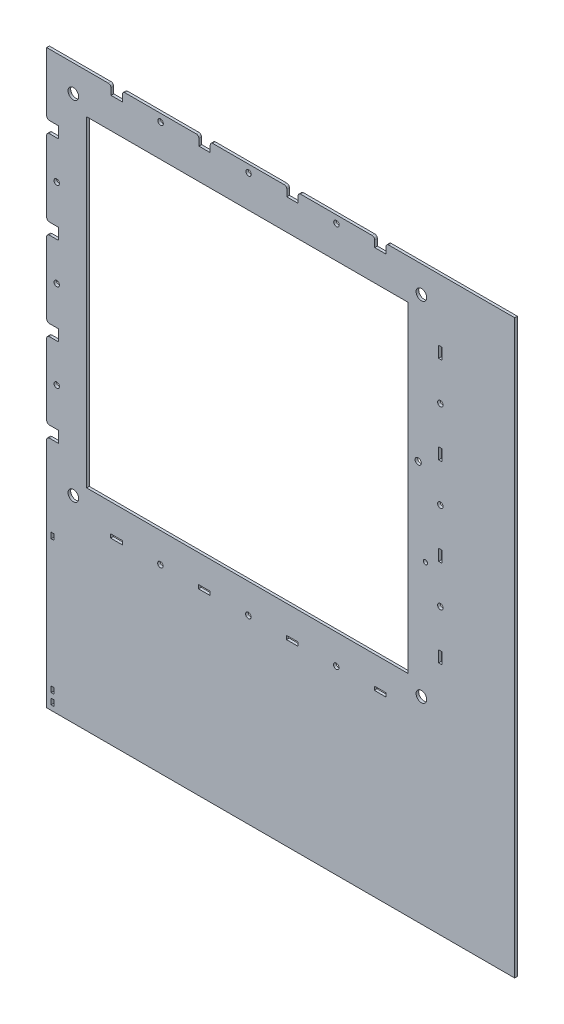
SolidWorks part; units mm, degrees
ref_plane "前视基准面" through (0, 0, 0) normal (0, 0, 1) x (1, 0, 0)
ref_plane "上视基准面" through (0, 0, 0) normal (0, 1, 0) x (1, 0, 0)
ref_plane "右视基准面" through (0, 0, 0) normal (1, 0, 0) x (0, 0, -1)
sketch "草图1" plane through (0, 0, 0) normal (0, 0, 1) x (1, 0, 0)
  line L0 (95.3243, -141.495) -> (104.1243, -141.495)
  line L1 (0.7243, -148.895) -> (0.7243, -142.895) construction
  line L2 (0.7243, -142.895) -> (33.7243, -142.895) construction
  line L3 (33.7243, -142.895) -> (66.7243, -142.895) construction
  line L4 (29.3243, -141.495) -> (38.1243, -141.495)
  line L5 (29.3243, -141.495) -> (29.3243, -144.295)
  line L6 (29.3243, -144.295) -> (38.1243, -144.295)
  line L7 (38.1243, -141.495) -> (38.1243, -144.295)
  line L8 (29.3243, -141.495) -> (38.1243, -144.295) construction
  line L9 (29.3243, -144.295) -> (38.1243, -141.495) construction
  line L10 (66.7243, -142.895) -> (99.7243, -142.895) construction
  line L11 (95.3243, -141.495) -> (95.3243, -144.295)
  line L12 (95.3243, -144.295) -> (104.1243, -144.295)
  line L13 (95.3243, -144.295) -> (104.1243, -141.495) construction
  line L14 (104.1243, -144.295) -> (104.1243, -141.495)
  line L15 (-36.6757, -141.495) -> (-36.6757, -144.295)
  line L16 (-27.8757, -141.495) -> (-36.6757, -141.495)
  line L17 (-27.8757, -141.495) -> (-27.8757, -144.295)
  line L18 (-27.8757, -144.295) -> (-36.6757, -144.295)
  line L19 (-93.8757, -141.495) -> (-93.8757, -144.295)
  line L20 (-102.6757, -144.295) -> (-102.6757, -141.495)
  line L21 (-93.8757, -141.495) -> (-102.6757, -141.495)
  line L22 (-93.8757, -144.295) -> (-102.6757, -144.295)
  line L23 (-141.8757, 95.705) -> (-141.8757, 104.205)
  line L24 (-144.3757, 95.705) -> (-144.3757, 104.205)
  line L25 (-144.3757, 104.205) -> (-141.8757, 104.205)
  line L26 (-141.8757, 95.705) -> (-144.3757, 95.705)
  line L27 (-141.8757, 29.705) -> (-141.8757, 38.205)
  line L28 (-141.8757, 38.205) -> (-144.3757, 38.205)
  line L29 (-144.3757, 29.705) -> (-144.3757, 38.205)
  line L30 (-141.8757, 29.705) -> (-144.3757, 29.705)
  line L31 (-141.8757, -27.795) -> (-144.3757, -27.795)
  line L32 (-141.8757, -27.795) -> (-141.8757, -36.295)
  line L33 (-144.3757, -27.795) -> (-144.3757, -36.295)
  line L34 (-141.8757, -36.295) -> (-144.3757, -36.295)
  line L35 (-141.8757, -93.795) -> (-141.8757, -102.295)
  line L36 (-144.3757, -93.795) -> (-144.3757, -102.295)
  line L37 (-141.8757, -93.795) -> (-144.3757, -93.795)
  line L38 (-144.3757, -102.295) -> (-141.8757, -102.295)
  line L39 (95.6243, 143.705) -> (104.1243, 143.705)
  line L40 (95.6243, 146.205) -> (104.1243, 146.205)
  line L41 (104.1243, 146.205) -> (104.1243, 143.705)
  line L42 (95.6243, 143.705) -> (95.6243, 146.205)
  line L43 (29.6243, 143.705) -> (38.1243, 143.705)
  line L44 (38.1243, 143.705) -> (38.1243, 146.205)
  line L45 (29.6243, 146.205) -> (38.1243, 146.205)
  line L46 (29.6243, 143.705) -> (29.6243, 146.205)
  line L47 (-27.8757, 143.705) -> (-27.8757, 146.205)
  line L48 (-27.8757, 143.705) -> (-36.3757, 143.705)
  line L49 (-27.8757, 146.205) -> (-36.3757, 146.205)
  line L50 (-36.3757, 143.705) -> (-36.3757, 146.205)
  line L51 (-93.8757, 143.705) -> (-102.3757, 143.705)
  line L52 (-93.8757, 146.205) -> (-102.3757, 146.205)
  line L53 (-93.8757, 143.705) -> (-93.8757, 146.205)
  line L54 (-102.3757, 146.205) -> (-102.3757, 143.705)
  line L55 (143.6243, -93.795) -> (143.6243, -102.295)
  line L56 (146.1243, -93.795) -> (146.1243, -102.295)
  line L57 (146.1243, -102.295) -> (143.6243, -102.295)
  line L58 (143.6243, -93.795) -> (146.1243, -93.795)
  line L59 (143.6243, -27.795) -> (143.6243, -36.295)
  line L60 (143.6243, -36.295) -> (146.1243, -36.295)
  line L61 (146.1243, -27.795) -> (146.1243, -36.295)
  line L62 (143.6243, -27.795) -> (146.1243, -27.795)
  line L63 (143.6243, 29.705) -> (146.1243, 29.705)
  line L64 (143.6243, 29.705) -> (143.6243, 38.205)
  line L65 (146.1243, 29.705) -> (146.1243, 38.205)
  line L66 (143.6243, 38.205) -> (146.1243, 38.205)
  line L67 (143.6243, 95.705) -> (143.6243, 104.205)
  line L68 (146.1243, 95.705) -> (146.1243, 104.205)
  line L69 (143.6243, 95.705) -> (146.1243, 95.705)
  line L70 (146.1243, 104.205) -> (143.6243, 104.205)
  line L71 (50.2243, -142.895) -> (50.2243, -127.895) construction
  line L72 (17.2243, -142.895) -> (17.2243, -127.895) construction
  line L73 (120.6507, 120.6507) -> (-120.6507, 120.6507)
  line L75 (99.7243, -142.895) -> (104.1243, -144.295) construction
  line L76 (150.6507, -150.6507) -> (150.6507, 150.6507) construction
  line L78 (-150.6507, -150.6507) -> (-150.6507, 150.6507)
  line L79 (150.6507, -150.6507) -> (-150.6507, 150.6507) construction
  line L80 (150.6507, 150.6507) -> (-150.6507, -150.6507) construction
  line L81 (-120.6507, -120.6507) -> (-120.6507, 120.6507)
  line L82 (120.6507, -120.6507) -> (-120.6507, -120.6507)
  line L83 (120.6507, -120.6507) -> (120.6507, 120.6507)
  line L84 (-150.6507, 150.6507) -> (-150.6507, 277.9507) construction
  line L85 (-150.6507, 277.9507) -> (150.6507, 277.9507) construction
  line L86 (150.6507, 277.9507) -> (150.6507, 150.6507) construction
  line L87 (150.6507, 150.6507) -> (-150.6507, 150.6507)
  line L88 (150.6507, 150.6507) -> (-150.6507, 150.6507) construction
  line L89 (-120.6507, 180.6507) -> (-120.6507, 247.9507) construction
  line L90 (-120.6507, 247.9507) -> (120.6507, 247.9507) construction
  line L91 (120.6507, 247.9507) -> (120.6507, 180.6507) construction
  line L92 (120.6507, 180.6507) -> (-120.6507, 180.6507) construction
  line L93 (120.6507, -180.6507) -> (120.6507, -248.6507) construction
  line L94 (-150.6507, -150.6507) -> (150.6507, -150.6507) construction
  line L95 (-150.6507, -150.6507) -> (-150.6507, -278.6507)
  line L96 (-150.6507, -278.6507) -> (150.6507, -278.6507)
  line L97 (150.6507, -150.6507) -> (150.6507, -278.6507) construction
  line L98 (150.6507, -150.6507) -> (-150.6507, -150.6507) construction
  line L99 (-120.6507, -248.6507) -> (120.6507, -248.6507) construction
  line L100 (-120.6507, -180.6507) -> (-120.6507, -248.6507) construction
  line L101 (-120.6507, -180.6507) -> (120.6507, -180.6507) construction
  line L103 (150.6507, 150.6507) -> (200.6507, 150.6507)
  line L106 (200.6507, 150.6507) -> (200.6507, -278.6507)
  line L110 (200.8743, -261.0808) -> (200.6507, -261.0808)
  line L115 (-145.0257, -270.745) -> (-147.3257, -270.745)
  line L116 (-145.0257, -270.745) -> (-145.0257, -275.045)
  line L117 (-145.0257, -275.045) -> (-147.3257, -275.045)
  line L118 (-147.3257, -270.745) -> (-147.3257, -275.045)
  line L119 (-145.0257, -262.745) -> (-147.3257, -262.745)
  line L120 (-145.0257, -262.745) -> (-145.0257, -267.045)
  line L121 (-145.0257, -267.045) -> (-147.3257, -267.045)
  line L122 (-147.3257, -262.745) -> (-147.3257, -267.045)
  line L123 (150.6507, -278.6507) -> (200.6507, -278.6507)
  line L125 (-145.0257, -162.745) -> (-147.3257, -162.745)
  line L126 (-145.0257, -162.745) -> (-145.0257, -167.045)
  line L127 (-145.0257, -167.045) -> (-147.3257, -167.045)
  line L128 (-147.3257, -162.745) -> (-147.3257, -167.045)
  circle A0 centre (0.7243, -142.895) radius 2.05
  circle A1 centre (66.7243, -142.895) radius 2.05
  circle A2 centre (-65.2757, -142.895) radius 2.05
  circle A3 centre (-143.1257, 66.955) radius 2.05
  circle A4 centre (-143.1257, 0.955) radius 2.05
  circle A5 centre (-143.1257, -65.045) radius 2.05
  circle A6 centre (66.8743, 144.955) radius 2.05
  circle A7 centre (0.8743, 144.955) radius 2.05
  circle A8 centre (-65.1257, 144.955) radius 2.05
  circle A9 centre (144.8743, -65.045) radius 2.05
  circle A10 centre (144.8743, 0.955) radius 2.05
  circle A11 centre (144.8743, 66.955) radius 2.05
  circle A12 centre (-130.6507, -130.6507) radius 4
  circle A18 centre (-130.6507, 130.6507) radius 4
  circle A19 centre (130.6507, 130.6507) radius 4
  circle A20 centre (130.6507, -130.6507) radius 4
  circle A21 centre (128.2349, 21.0459) radius 2.333
  circle A22 centre (133.7092, -41.7691) radius 1.6011
  point P25 (0, 0)
  dimension "D4" = 66
  dimension "D5" = 33
  dimension "D6" = 4.1
  dimension "D9" = 30
  dimension "D13" = 8
  dimension "D1" = 8.8
  dimension "D2" = 2.8
  dimension "D3" = 30
  dimension "D7" = 8.8
  dimension "D8" = 2.8
  dimension "D11" = 127.3
  dimension "D10" = 301.3014
  dimension "D14" = 4
  dimension "D15" = 128
  dimension "D16" = 50
  dimension "D12" = 30
extrude "凸台-拉伸1" add sketch "草图1" along normal blind 2
sketch "草图2" plane through (0, 0, 2) normal (0, 0, 1) x (1, 0, 0)
  line L1 (-144.3757, -102.295) -> (-159.7471, -102.295)
  line L2 (-144.3757, -102.295) -> (-144.3757, -93.7809)
  line L3 (-144.3757, -93.7809) -> (-159.7471, -93.7809)
  line L4 (-159.7471, -102.295) -> (-159.7471, -93.7809)
  line L5 (-144.3757, -36.295) -> (-153.2048, -36.295)
  line L6 (-144.3757, -36.295) -> (-144.3757, -27.795)
  line L7 (-144.3757, -27.795) -> (-153.2048, -27.795)
  line L8 (-153.2048, -36.295) -> (-153.2048, -27.795)
  line L9 (-144.3757, 29.705) -> (-154.7113, 29.705)
  line L10 (-144.3757, 29.705) -> (-144.3757, 38.205)
  line L11 (-144.3757, 38.205) -> (-154.7113, 38.205)
  line L12 (-154.7113, 29.705) -> (-154.7113, 38.205)
  line L13 (-144.3757, 95.705) -> (-154.7113, 95.705)
  line L14 (-144.3757, 95.705) -> (-144.3757, 104.205)
  line L15 (-144.3757, 104.205) -> (-154.7113, 104.205)
  line L16 (-154.7113, 95.705) -> (-154.7113, 104.205)
  line L17 (-102.3757, 146.205) -> (-93.8757, 146.205)
  line L18 (-102.3757, 146.205) -> (-102.3757, 151.5027)
  line L19 (-102.3757, 151.5027) -> (-93.8757, 151.5027)
  line L20 (-93.8757, 146.205) -> (-93.8757, 151.5027)
  line L21 (-36.3757, 146.205) -> (-27.8757, 146.205)
  line L22 (-36.3757, 146.205) -> (-36.3757, 152.6506)
  line L23 (-36.3757, 152.6506) -> (-27.8757, 152.6506)
  line L24 (-27.8757, 146.205) -> (-27.8757, 152.6506)
  line L25 (29.6243, 146.205) -> (38.1243, 146.205)
  line L26 (29.6243, 146.205) -> (29.6243, 152.6506)
  line L27 (29.6243, 152.6506) -> (38.1243, 152.6506)
  line L28 (38.1243, 146.205) -> (38.1243, 152.6506)
  line L29 (95.6243, 146.205) -> (104.1243, 146.205)
  line L30 (95.6243, 146.205) -> (95.6243, 152.0898)
  line L31 (95.6243, 152.0898) -> (104.1243, 152.0898)
  line L32 (104.1243, 146.205) -> (104.1243, 152.0898)
extrude "切除-拉伸1" cut sketch "草图2" against normal blind 2
fillet "圆角1" radius 2 16 edges at (-150.6507, -102.295, 1) (-150.6507, -93.7809, 1) (-150.6507, -36.295, 1) (-150.6507, -27.795, 1) (-150.6507, 29.705, 1) (-150.6507, 38.205, 1) (-150.6507, 95.705, 1) (-150.6507, 104.205, 1) (-102.3757, 150.6507, 1) (-93.8757, 150.6507, 1) (-36.3757, 150.6507, 1) (-27.8757, 150.6507, 1) (29.6243, 150.6507, 1) (38.1243, 150.6507, 1) (95.6243, 150.6507, 1) (104.1243, 150.6507, 1)
